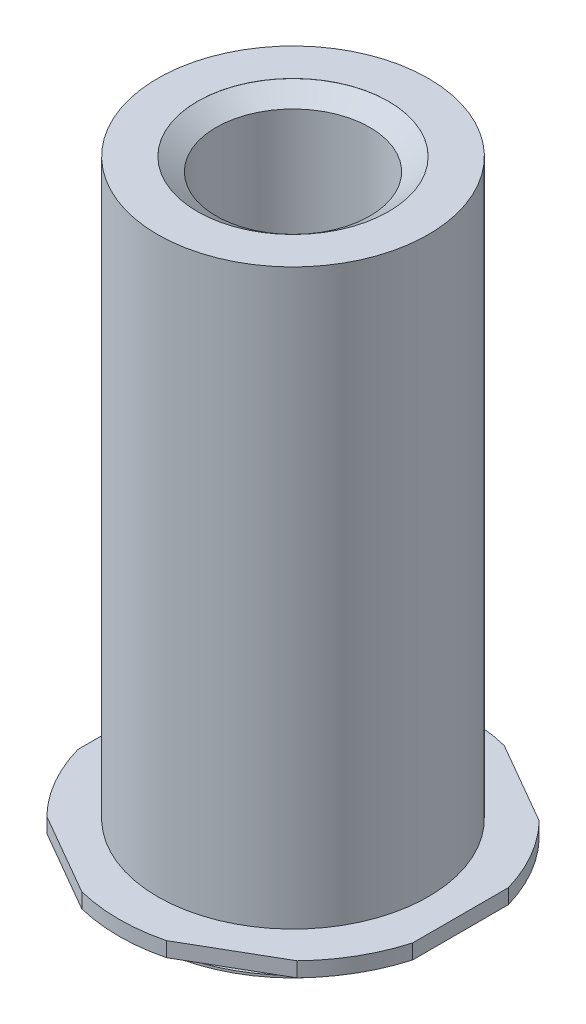
SolidWorks part; units mm, degrees
revolve "Body" add sketch "BodySke"
sketch "BodySke" plane through (0, 0, 0) normal (0, 0, 1) x (1, 0, 0)
  line L0 (4.7321, 0) -> (5.7851, 0)
  line L1 (5.7851, 0) -> (5.7851, 0.4915)
  line L2 (5.7851, 0.4915) -> (4.4958, 0.4915)
  line L3 (2.5527, 19.5415) -> (2.5527, 10.0165)
  line L4 (0, -0.6007) -> (4.9403, -0.6007)
  line L5 (4.9403, -0.6007) -> (4.9403, -0.5245)
  line L6 (4.9403, -0.5245) -> (4.7321, -0.1638)
  line L7 (1.016, 18.2715) -> (3.6522, 18.2715) construction
  line L8 (4.4958, 19.5415) -> (2.5527, 19.5415)
  line L9 (0, 0) -> (0, 15.24) construction
  line L10 (4.7321, -0.1638) -> (4.7321, 0)
  line L11 (4.4958, 19.5415) -> (4.4958, 0.4915)
  line L12 (0, 10.0165) -> (2.5527, 10.0165)
  line L13 (0, 10.0165) -> (0, -0.6007)
  line L14 (1.016, 10.0165) -> (3.6522, 10.0165) construction
  line L15 (1.016, 10.0165) -> (3.6522, 10.0165) construction
  dimension "E_dia" = 11.5702
  dimension "C_dia" = 9.8806
  dimension "A_ht" = 0.6007
  dimension "Thread_min" = 5.1054
  dimension "C_len" = 0.0762
  dimension "Clinching_ht" = 0.1638
  dimension "D1" = 60
  dimension "Thickness" = 1.0922
  dimension "B_dia" = 8.9916
  dimension "Length" = 19.05
  dimension "Thread_limit" = 9.525
  dimension "Advance" = 1.27
  dimension "Thread_depth" = 9.525
  dimension "Drill_depth" = 9.525
cosmetic thread "ThreadCosmetic" [suppressed]
revolve "EndChamfer" cut sketch "EndChamferSke" angle 360 about L0
sketch "EndChamferSke" plane through (0, 0, 0) normal (0, 0, 1) x (1, 0, 0)
  line L0 (0, -2.54) -> (0, 7.62) construction
  line L1 (0, 0) -> (0, 15.24) construction
  line L6 (3.175, 19.539) -> (2.5527, 19.1034)
  line L7 (3.175, 19.539) -> (3.175, 19.7955)
  line L8 (2.5527, 19.1034) -> (2.5527, 19.7955)
  line L9 (3.175, 19.7955) -> (2.5527, 19.7955)
  line L10 (4.4958, 19.5415) -> (-4.4958, 19.5415) construction
  dimension "D1" = 0.254
  dimension "Thread_nominal" = 6.35
  dimension "D2" = 34.99
  dimension "Thread_min" = 5.1054
  dimension "Inset" = 0.0025
revolve "TapDrill" cut sketch "TapDriSke" angle 360 about L0
sketch "TapDriSke" plane through (0, 0, 0) normal (0, 0, 1) x (1, 0, 0)
  line L0 (0, 0) -> (0, 15.24) construction
  line L1 (0, 0) -> (0, 15.24) construction
  line L2 (2.5527, 3.6665) -> (2.5527, 19.5415)
  line L3 (4.4958, 19.5415) -> (-4.4958, 19.5415) construction
  line L4 (2.5527, 3.6665) -> (0, 2.6091)
  line L5 (0, 2.6091) -> (0, 19.5415)
  line L6 (0, 19.5415) -> (2.5527, 19.5415)
  line L7 (2.5527, 10.0165) -> (2.5527, 19.5415) construction
  line L8 (0, 2.6091) -> (-2.5527, 3.6665) construction
  line L9 (-2.5527, 19.5415) -> (-2.5527, 10.0165) construction
  dimension "D1" = 135
ref_plane "Plane1" through (0, 0, 0) normal (0, 0, 1) x (1, 0, 0)
ref_plane "Plane2" through (0, 0, 0) normal (0, 1, 0) x (1, 0, 0)
ref_plane "Plane3" through (0, 0, 0) normal (1, 0, 0) x (0, 0, -1)
ref_plane "Plane4" through (0, -0.5486, 0) normal (0, 1, 0) x (-1, 0, 0)
sketch "ThdSchSke" plane through (0, 0, 0) normal (0, 0, 1) x (1, 0, 0)
  line L0 (0, -5.08) -> (0, 7.62) construction
  line L1 (0, 0) -> (0, 15.24) construction
  line L2 (0, 19.539) -> (3.175, 19.539) construction
  line L3 (3.175, 19.539) -> (-3.175, 19.539) construction
  line L4 (3.175, 19.539) -> (2.5527, 19.9747)
  line L6 (3.175, 19.539) -> (2.5527, 19.1032)
  line L7 (2.5527, 19.9747) -> (2.5527, 19.1032)
  dimension "Thread_min" = 5.1054
revolve "ThreadSchematic" [suppressed] cut sketch "ThdSchSke" angle 360 about L0
pattern_linear "ThdSchPat" [suppressed]
sketch "HexDieSke" plane through (0, 0.4915, 0) normal (0, 1, 0) x (-1, 0, 0)
  line L0 (0, 6.4231) -> (5.5626, 3.2116)
  line L1 (5.5626, 3.2116) -> (5.5626, -3.2116)
  line L2 (5.5626, -3.2116) -> (0, -6.4231)
  line L3 (0, -6.4231) -> (-5.5626, -3.2116)
  line L4 (-5.5626, -3.2116) -> (-5.5626, 3.2116)
  line L5 (-5.5626, 3.2116) -> (0, 6.4231)
  circle A1 centre (0, 0) radius 5.5626 construction
  circle A2 centre (0, 0) radius 6.4231 construction
  circle A3 centre (0, 0) radius 6.4653
extrude "HexDie" cut sketch "HexDieSke" against normal blind 0.4915
equation "' \"Length@BodySke\" = 0.75"
equation "' \"Thickness@BodySke\" = 0.043"
equation "' \"B_dia@BodySke\" = 0.354"
equation "' \"C_dia@BodySke\" = 0.389"
equation "' \"Width_across_flats@HexDieSke\" = 0.438"
equation "' \"E_dia@BodySke\" = \"Width_across_flats@HexDieSke\" * 1.04 ' varies by type (1.04 or 1.16)"
equation "' \"Thread_depth@BodySke\" = 0.375"
equation "' \"Drill_depth@BodySke\" = 0.375"
equation "' \"Advance@BodySke\" = 0.05"
equation "' \"Thread_min@BodySke\" = 0.201"
equation "' \"Thread_nominal@ThreadCosmetic\" = 0.25"
equation "\"Thread_limit@BodySke\" = ((sgn( \"Length@BodySke\" - \"Thread_depth@BodySke\" )-1)*( \"Length@BodySke\" - \"Thread_depth@BodySke\" ))/-2+ \"Thread_depth@BodySke\""
equation "\"Depth@TapDriSke\" = \"Thread_limit@BodySke\" + \"Advance@BodySke\" * 5"
equation "\"Depth@TapDriSke\" = ((sgn( \"Depth@TapDriSke\" - \"Drill_depth@BodySke\" )+1)*( \"Depth@TapDriSke\" - \"Drill_depth@BodySke\" ))/2 +\"Drill_depth@BodySke\""
equation "\"A_ht@BodySke\" = \"Thickness@BodySke\" * 0.55"
equation "\"Clinching_ht@BodySke\" = \"Thickness@BodySke\" * 0.15"
equation "\"C_len@BodySke\" =  0.003"
equation "\"Depth@HexDie\" = \"Thickness@BodySke\" - \"A_ht@BodySke\""
equation "\"OD@HexDieSke\" =  \"Width_across_flats@HexDieSke\" * 1.16 + 0.001"
equation "\"Thread_nominal@EndChamferSke\" = \"Thread_nominal@ThreadCosmetic\""
equation "\"Thread_min@EndChamferSke\" = \"Thread_min@BodySke\""
equation "\"D2@EndChamferSke\" = \"Vee_angle@ThdSchSke\" / 2 - 0.01"
equation "\"Thread_nominal@ThdSchSke\" = \"Thread_nominal@ThreadCosmetic\""
equation "\"Thread_min@ThdSchSke\" = \"Thread_min@BodySke\""
equation "\"Num_threads@ThdSchPat\" = int(  ( \"Thread_limit@BodySke\" - \"Inset@EndChamferSke\" ) / \"Advance@BodySke\" + 0.999 )  + 1"
equation "\"Advance@ThdSchPat\" = (  \"Thread_limit@BodySke\" - \"Inset@EndChamferSke\" ) /  (\"Num_threads@ThdSchPat\" - 1) 'relax it"
